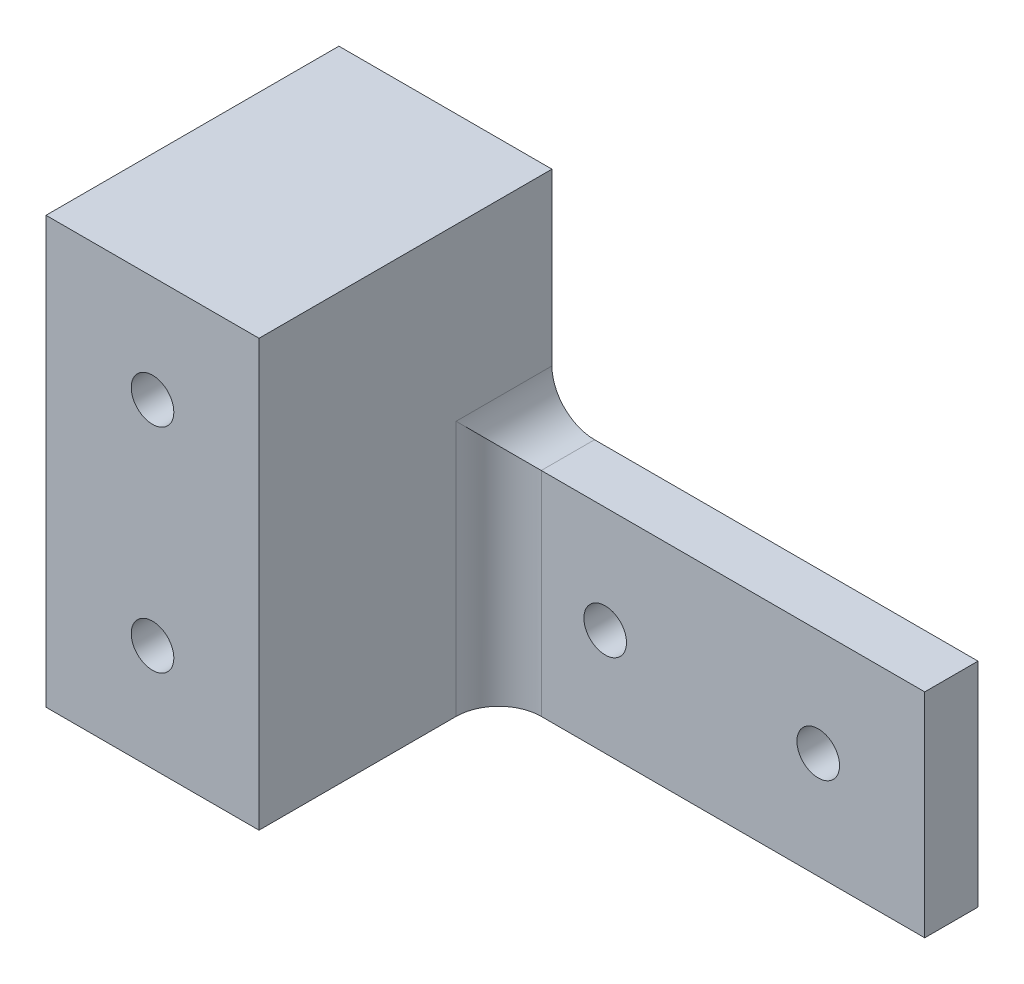
SolidWorks part; units mm, degrees
ref_plane "Front Plane" through (0, 0, 0) normal (0, 0, 1) x (1, 0, 0)
ref_plane "Top Plane" through (0, 0, 0) normal (0, 1, 0) x (1, 0, 0)
ref_plane "Right Plane" through (0, 0, 0) normal (1, 0, 0) x (0, 0, -1)
sketch "Sketch1" plane through (0, 0, 0) normal (0, 0, 1) x (1, 0, 0)
  line L0 (0, 0) -> (0, 50.8)
  line L1 (0, 50.8) -> (25.4, 50.8)
  line L2 (25.4, 50.8) -> (25.4, 25.4)
  line L3 (25.4, 25.4) -> (76.2, 25.4)
  line L4 (76.2, 25.4) -> (76.2, 0)
  line L5 (76.2, 0) -> (0, 0)
  dimension "D1" = 50.8
  dimension "D2" = 25.4
  dimension "3" = 76.2
extrude "Boss-Extrude1" add sketch "Sketch1" along normal blind 34.925
sketch "Sketch2" plane through (0, 0, 34.925) normal (0, 0, 1) x (1, 0, 0)
  line L0 (25.4, 50.8) -> (0, 50.8) construction
  line L1 (25.4, 25.4) -> (25.4, 50.8) construction
  line L2 (0, 0) -> (76.2, 0) construction
  circle A0 centre (12.7, 38.1) radius 2.54
  circle A1 centre (12.7, 12.7) radius 2.54
  circle A2 centre (38.1, 12.7) radius 2.54
  circle A3 centre (63.5, 12.7) radius 2.54
  dimension "D1" = 5.08
  dimension "D2" = 12.7
  dimension "D3" = 12.7
  dimension "D4" = 12.7
  dimension "D5" = 3
extrude "Cut-Extrude1" cut sketch "Sketch2" against normal through all
sketch "Sketch3" plane through (0, 0, 34.925) normal (0, 0, 1) x (1, 0, 0)
  line L0 (25.4, 50.8) -> (0, 50.8) construction
  line L1 (0, 0) -> (4.7625, 0)
  line L2 (0, 0) -> (0, 50.8)
  line L3 (0, 50.8) -> (4.7625, 50.8)
  line L4 (4.7625, 0) -> (4.7625, 50.8)
  dimension "D1" = 4.7625
sketch "Sketch4" plane through (0, 0, 0) normal (0, -1, 0) x (1, 0, 0)
  line L5 (76.2, 34.925) -> (25.4, 34.925)
  line L6 (76.2, 34.925) -> (76.2, 6.35)
  line L7 (76.2, 6.35) -> (25.4, 6.35)
  line L8 (25.4, 34.925) -> (25.4, 6.35)
  dimension "D1" = 28.575
  dimension "D2" = 50.8
extrude "Cut-Extrude3" cut sketch "Sketch4" against normal through all
fillet "Fillet1" radius 5.08 2 edges at (25.4, 25.4, 3.175) (25.4, 12.7, 6.35)
sketch "Sketch5" plane through (0, 0, 0) normal (0, 0, -1) x (-1, 0, 0)
  circle A0 centre (-12.7, 38.1) radius 6.35
  dimension "D1" = 12.7
extrude "Cut-Extrude4" cut sketch "Sketch5" against normal blind 22.225
